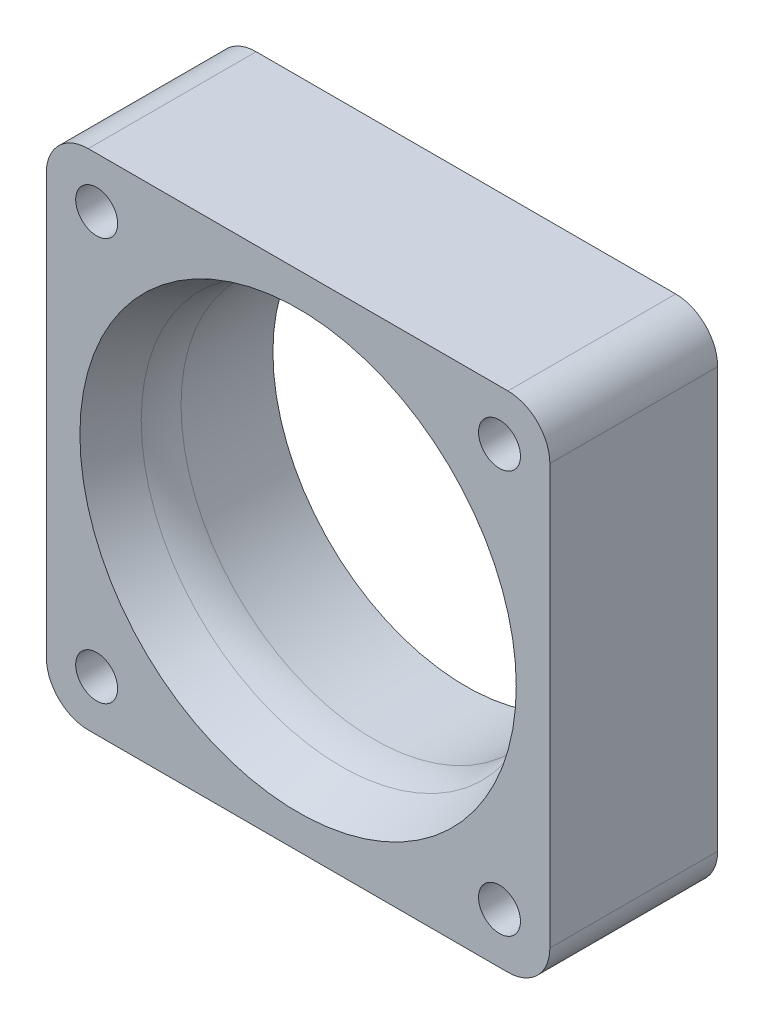
SolidWorks part; units mm, degrees
material "ABS"
ref_plane "Front Plane" through (0, 0, 0) normal (0, 0, 1) x (1, 0, 0)
ref_plane "Top Plane" through (0, 0, 0) normal (0, 1, 0) x (1, 0, 0)
ref_plane "Right Plane" through (0, 0, 0) normal (1, 0, 0) x (0, 0, -1)
sketch "Sketch1" plane through (0, 0, 0) normal (0, 0, 1) x (1, 0, 0)
  line L1 (-15, -15) -> (15, -15)
  line L2 (-15, -15) -> (-15, 15)
  line L3 (-15, 15) -> (15, 15)
  line L4 (15, -15) -> (15, 15)
  line L5 (-15, -15) -> (15, 15) construction
  line L6 (-15, 15) -> (15, -15) construction
  point P0 (0, 0)
  dimension "D1" = 30
  dimension "D2" = 30
extrude "Boss-Extrude1" add sketch "Sketch1" along normal blind 10
fillet "Fillet1" radius 2.5 4 edges at (-15, -15, 5) (15, -15, 5) (-15, 15, 5) (15, 15, 5)
sketch "Sketch2" plane through (0, 0, 10) normal (0, 0, 1) x (1, 0, 0)
  line L1 (-12, -12) -> (12, -12) construction
  line L2 (-12, -12) -> (-12, 12) construction
  line L3 (-12, 12) -> (12, 12) construction
  line L4 (12, -12) -> (12, 12) construction
  line L5 (-12, -12) -> (12, 12) construction
  line L6 (-12, 12) -> (12, -12) construction
  circle A0 centre (-12, 12) radius 1.25
  circle A1 centre (12, 12) radius 1.25
  circle A2 centre (12, -12) radius 1.25
  circle A3 centre (-12, -12) radius 1.25
  point P0 (0, 0)
  dimension "D3" = 2.5
  dimension "D1" = 24
  dimension "D2" = 24
extrude "Cut-Extrude1" cut sketch "Sketch2" against normal through all
sketch "Sketch4" plane through (0, 0, 0) normal (1, 0, 0) x (0, 0, -1)
  line L0 (0, 0) -> (-10, 0)
  line L1 (0, -12.5) -> (0, 12.5) construction
  line L2 (-10, -12.5) -> (-10, 12.5) construction
  line L3 (-10, 0) -> (-10, 13)
  line L4 (0, 11.5) -> (-6.5, 11.5)
  line L5 (0, 11.5) -> (0, 0)
  line L6 (-6.5, 11.5) -> (-10, 13)
  line L7 (0, 0) -> (-10, 0) construction
  dimension "D1" = 1.5
  dimension "D2" = 13
  dimension "D3" = 3.5
revolve "Cut-Revolve1" cut sketch "Sketch4" angle 360 about L7
fillet "Fillet2" radius 5 1 edges at (-11.5, 0, 6.5)
